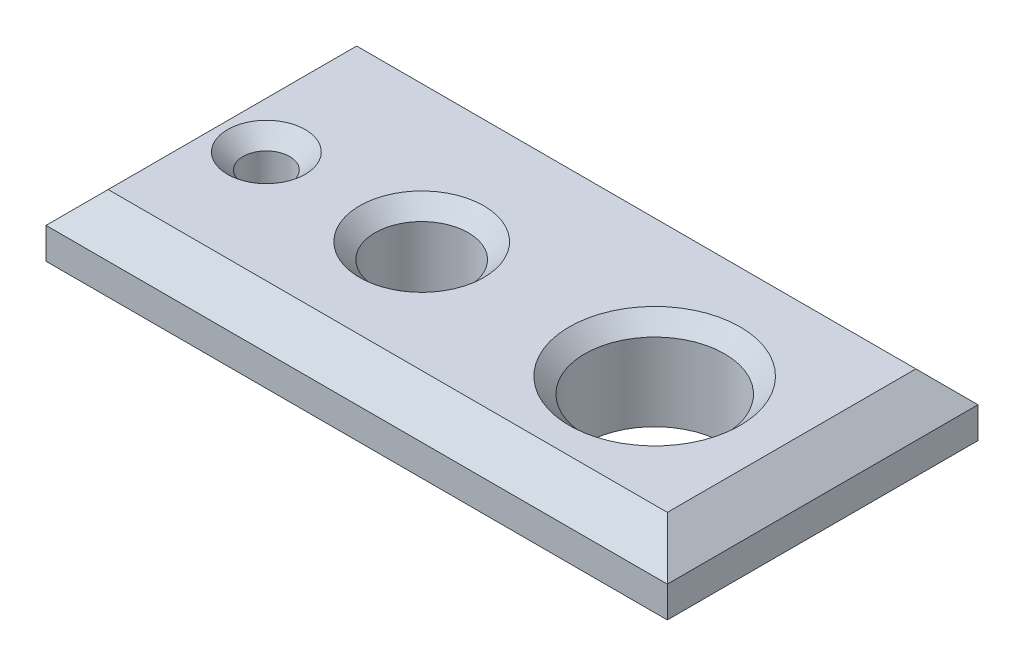
SolidWorks part; units mm, degrees
ref_plane "Front Plane" through (0, 0, 0) normal (0, 0, 1) x (1, 0, 0)
ref_plane "Top Plane" through (0, 0, 0) normal (0, 1, 0) x (1, 0, 0)
ref_plane "Right Plane" through (0, 0, 0) normal (1, 0, 0) x (0, 0, -1)
sketch "Sketch2" plane through (0, 0, 0) normal (0, 1, 0) x (1, 0, 0)
  line L0 (-173.6972, 0) -> (168.8196, 0) construction
  line L1 (-100, 54.0691) -> (100, 54.0691)
  line L2 (100, 54.0691) -> (100, -45.9309)
  line L3 (100, -45.9309) -> (-100, -45.9309)
  line L4 (-100, -45.9309) -> (-100, 54.0691)
  circle A0 centre (-75, 0) radius 7.5
  circle A1 centre (-25, 0) radius 15
  circle A2 centre (50, 0) radius 22.5
  point P13 (-100, 4.0691)
  point P14 (0, 0)
  point P15 (0, 0)
  point P16 (0, -45.9309)
  dimension "D6" = 15
  dimension "D7" = 30
  dimension "D8" = 45
  dimension "D1" = 25
  dimension "D2" = 50
  dimension "D3" = 75
  dimension "D4" = 200
  dimension "D5" = 100
extrude "Boss-Extrude1" add sketch "Sketch2" along normal blind 30
chamfer "Chamfer2" distance 5 angle 45 3 edges at (50, 30, 22.5) (-25, 30, 15) (-75, 30, 7.5)
chamfer "Chamfer3" distance 10 angle 45 8 edges at (0, 30, -54.0691) (100, 30, -4.0691) (0, 30, 45.9309) (-100, 30, -4.0691) (100, 0, -4.0691) (0, 0, -54.0691) (-100, 0, -4.0691) (0, 0, 45.9309)
